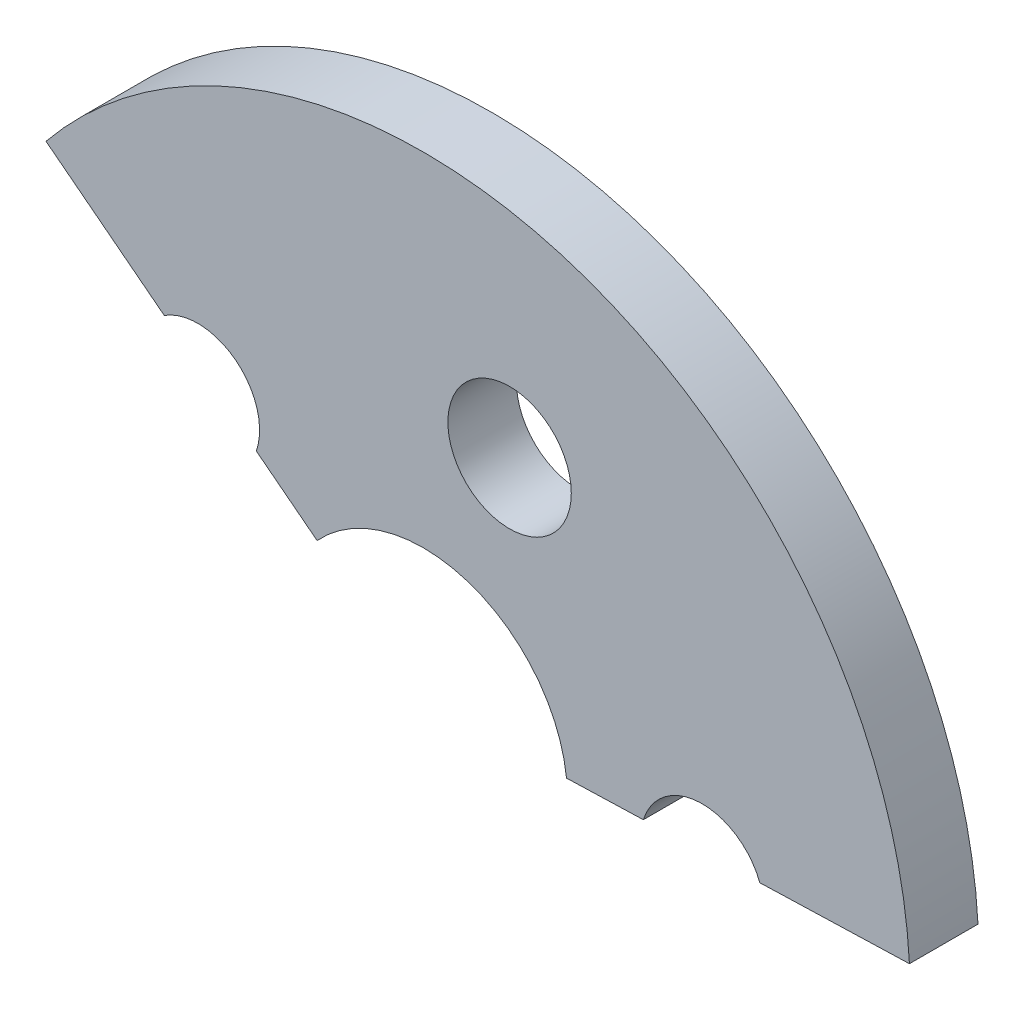
SolidWorks part; units mm, degrees
ref_plane "Front Plane" through (0, 0, 0) normal (0, 0, 1) x (1, 0, 0)
ref_plane "Top Plane" through (0, 0, 0) normal (0, 1, 0) x (1, 0, 0)
ref_plane "Right Plane" through (0, 0, 0) normal (1, 0, 0) x (0, 0, -1)
sketch "Sketch12" plane through (0, 0, 0) normal (0, 0, 1) x (1, 0, 0)
  line L0 (-5.8868, 18.1176) -> (15.4118, 11.1973) construction
  line L1 (0, 38.1) -> (22.3946, 30.8235) construction
  line L2 (11.1973, 34.4618) -> (4.7625, 14.6575) construction
  circle A0 centre (0, 0) radius 50.165
  circle A2 centre (-22.3946, 30.8235) radius 9.5631
  circle A3 centre (0, 38.1) radius 9.5631
  circle A4 centre (22.3946, 30.8235) radius 9.5631
  circle A5 centre (36.2353, 11.7735) radius 9.5631
  circle A6 centre (15.4118, 11.1973) radius 9.6393
  circle A7 centre (-5.8868, 18.1176) radius 9.6393
  circle A8 centre (0, 0) radius 8.255
  circle A9 centre (7.9799, 24.5596) radius 5.715
  point P18 (7.9799, 24.5596)
  dimension "D1" = 19.1262
  dimension "D2" = 16.51
  dimension "D3" = 100.33
  dimension "D4" = 19.2786
  dimension "D15" = 11.43
  dimension "D5" = 15.4118
  dimension "D6" = 22.3946
  dimension "D7" = 36.2353
  dimension "D8" = 5.8868
  dimension "D9" = 22.3946
  dimension "D10" = 11.1973
  dimension "D11" = 11.7735
  dimension "D12" = 18.1176
  dimension "D13" = 30.8235
  dimension "D14" = 38.1
sketch "Sketch13" plane through (0, 0, 0) normal (0, 0, 1) x (1, 0, 0)
  line L1 (-34.961, 28.4672) -> (-9.8479, 8.9912)
  line L2 (22.3946, 30.8235) -> (0, 38.1) construction
  line L3 (0, 0) -> (11.1973, 34.4618) construction
  line L4 (45.0167, 2.4809) -> (13.252, 1.4856)
  arc A0 (13.252, 1.4856) -> (-9.8479, 8.9912) centre (0, 0) ccw
  arc A12 (45.0167, 2.4809) -> (-34.961, 28.4672) centre (0, 0) ccw
  point P15 (11.1973, 34.4618)
  dimension "D1" = 13.335
  dimension "D2" = 45.085
  dimension "D3" = 13.252
  dimension "D4" = 45.0167
extrude "Boss-Extrude1" add sketch "Sketch13" along normal blind 6.35
sketch "Sketch14" plane through (0, 0, 0) normal (0, 0, 1) x (1, 0, 0)
  circle A0 centre (36.2353, 11.7735) radius 1.27 construction
  circle A1 centre (15.4118, 11.1973) radius 1.27 construction
  circle A2 centre (-5.8868, 18.1176) radius 1.27 construction
  circle A3 centre (-22.3946, 30.8235) radius 1.27 construction
  point P0 (36.2353, 11.7735)
  point P1 (15.4118, 11.1973)
  point P3 (-5.8868, 18.1176)
  point P5 (-22.3946, 30.8235)
  point P7 (22.3946, 30.8235)
  point P9 (0, 38.1)
  dimension "D1" = 2.54
  dimension "D2" = 2.54
  dimension "D3" = 2.54
  dimension "D4" = 2.54
sketch "Sketch15" plane through (0, 0, 6.35) normal (0, 0, 1) x (1, 0, 0)
  line L0 (0, 0) -> (-5.8868, 18.1176) construction
  line L1 (0, 0) -> (15.4118, 11.1973) construction
  line L2 (13.252, 1.4856) -> (45.0167, 2.4809) construction
  line L3 (-34.961, 28.4672) -> (-9.8479, 8.9912) construction
  line L4 (13.252, 1.4856) -> (31.1594, 2.0467)
  line L5 (-24.0055, 19.9709) -> (-15.4753, 13.3554)
  circle A0 centre (7.9799, 24.5596) radius 5.715 construction
  circle A1 centre (7.9799, 24.5596) radius 5.715
  arc A2 (-24.0055, 19.9709) -> (-15.4753, 13.3554) centre (-20.8917, 15.1787) cw
  arc A3 (20.3699, 1.7086) -> (31.1594, 2.0467) centre (25.8235, 0) cw
  line M6 (-34.961, 28.4672) -> (-9.8479, 8.9912)
extrude "Cut-Extrude1" cut sketch "Sketch15" against normal through all contours A2 M6 | A1 | A3 L4
